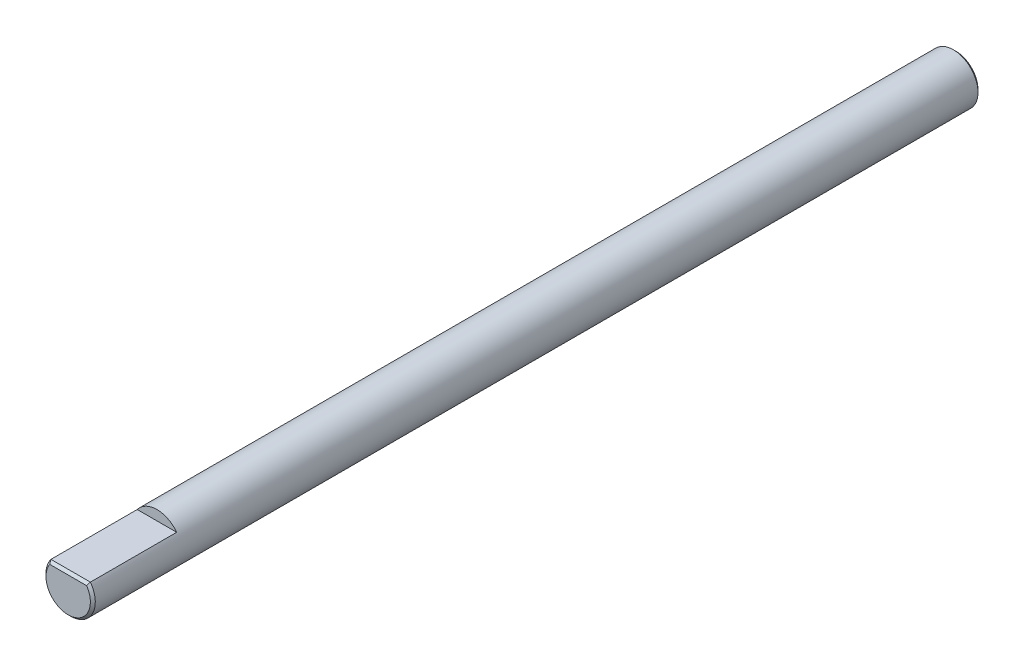
SolidWorks part; units mm, degrees
ref_plane "Front Plane" through (0, 0, 0) normal (0, 0, 1) x (1, 0, 0)
ref_plane "Top Plane" through (0, 0, 0) normal (0, 1, 0) x (1, 0, 0)
ref_plane "Right Plane" through (0, 0, 0) normal (1, 0, 0) x (0, 0, -1)
sketch "Sketch1" plane through (0, 0, 0) normal (0, 0, 1) x (1, 0, 0)
  circle A0 centre (0, 0) radius 2.5
  dimension "D1" = 5
extrude "Boss-Extrude1" add sketch "Sketch1" along normal blind 90
sketch "Sketch2" plane through (0, 0, 90) normal (0, 0, 1) x (1, 0, 0)
  line L0 (-2.4541, 1.5) -> (2.1518, 1.5)
  arc A0 (-2.4541, 1.5) -> (2.1518, 1.5) centre (-0.1512, 2.0286) cw
  dimension "D1" = 1.5
extrude "Cut-Extrude1" cut sketch "Sketch2" against normal blind 9
chamfer "Chamfer1" distance 0.25 angle 45 3 edges at (2.5, 0, 0) (0, -2.5, 90) (0, 1.5, 90)
